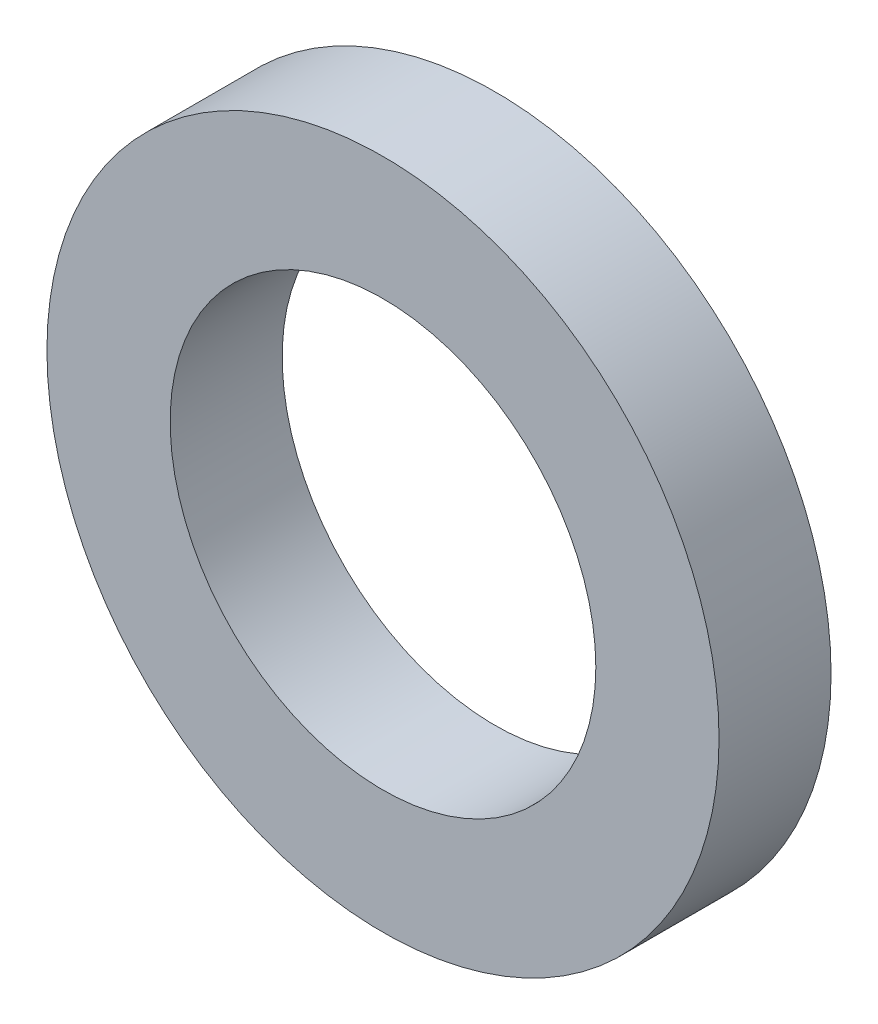
SolidWorks part; units mm, degrees
ref_plane "Front Plane" through (0, 0, 0) normal (0, 0, 1) x (1, 0, 0)
ref_plane "Top Plane" through (0, 0, 0) normal (0, 1, 0) x (1, 0, 0)
ref_plane "Right Plane" through (0, 0, 0) normal (1, 0, 0) x (0, 0, -1)
sketch "Sketch1" plane through (0, 0, 0) normal (0, 0, 1) x (1, 0, 0)
  circle A0 centre (0, 0) radius 3
  circle A1 centre (0, 0) radius 1.9
  dimension "D1" = 6
  dimension "D2" = 3.8
extrude "Boss-Extrude1" add sketch "Sketch1" along normal mid plane 1
